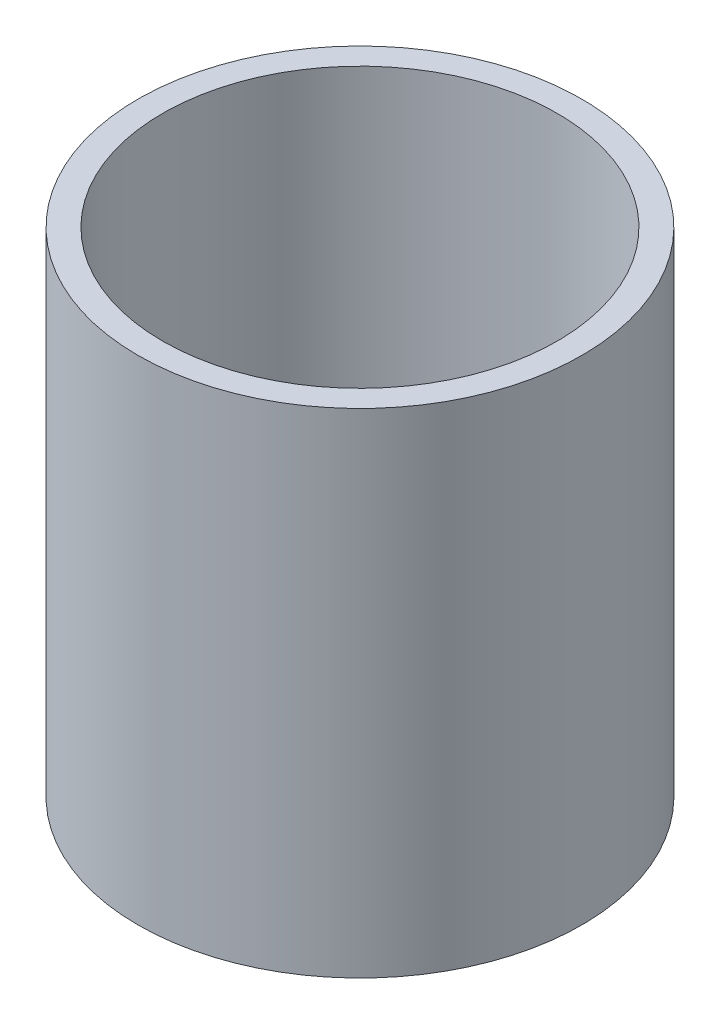
SolidWorks part; units mm, degrees
ref_plane "Front Plane" through (0, 0, 0) normal (0, 0, 1) x (1, 0, 0)
ref_plane "Top Plane" through (0, 0, 0) normal (0, 1, 0) x (1, 0, 0)
ref_plane "Right Plane" through (0, 0, 0) normal (1, 0, 0) x (0, 0, -1)
sketch "Sketch1" plane through (0, 0, 0) normal (0, 1, 0) x (1, 0, 0)
  circle A0 centre (0, 0) radius 9
extrude "Boss-Extrude1" add sketch "Sketch1" along normal blind 20
sketch "Sketch2" plane through (0, 20, 0) normal (0, 1, 0) x (1, 0, 0)
  circle A0 centre (0, 0) radius 8
extrude "Cut-Extrude1" cut sketch "Sketch2" against normal through all
